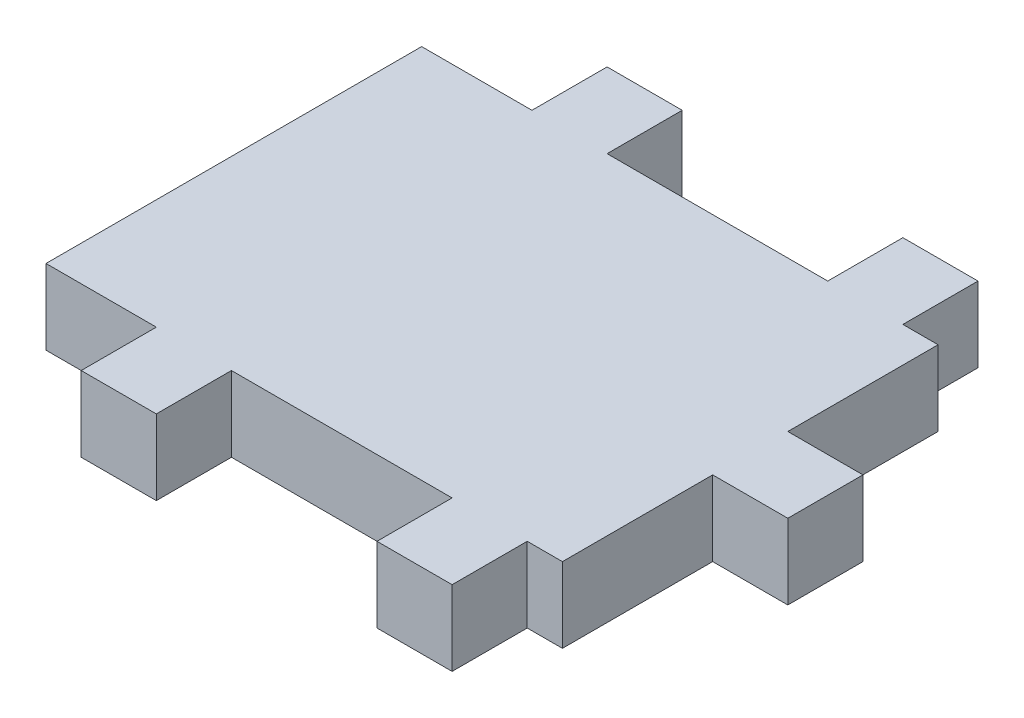
SolidWorks part; units mm, degrees
material "6061 Alloy"
ref_plane "Front" through (0, 0, 0) normal (0, 0, 1) x (1, 0, 0)
ref_plane "Top" through (0, 0, 0) normal (0, 1, 0) x (1, 0, 0)
ref_plane "Right" through (0, 0, 0) normal (1, 0, 0) x (0, 0, -1)
sketch "Sketch3" plane through (0, 0, 0) normal (0, 1, 0) x (1, 0, 0)
  line L1 (-43.65, -31.75) -> (43.65, -31.75)
  line L2 (-43.65, -31.75) -> (-43.65, 31.75)
  line L3 (-43.65, 31.75) -> (43.65, 31.75)
  line L4 (43.65, -31.75) -> (43.65, 31.75)
  line L5 (-43.65, -31.75) -> (43.65, 31.75) construction
  line L6 (-43.65, 31.75) -> (43.65, -31.75) construction
  point P0 (0, 0)
  dimension "D1" = 87.3
  dimension "D2" = 63.5
extrude "Boss-Extrude3" add sketch "Sketch3" along normal blind 12.7
sketch "Sketch4" plane through (43.65, 0, 0) normal (1, 0, 0) x (0, 0, -1)
  line L0 (0, 0) -> (0, 12.7) construction
  line L1 (-31.75, 12.7) -> (31.75, 12.7) construction
  line L3 (-6.35, 0) -> (6.35, 0)
  line L4 (-6.35, 0) -> (-6.35, 12.7)
  line L5 (-6.35, 12.7) -> (6.35, 12.7)
  line L6 (6.35, 0) -> (6.35, 12.7)
  line L7 (-6.35, 0) -> (6.35, 12.7) construction
  line L8 (-6.35, 12.7) -> (6.35, 0) construction
  point P5 (0, 6.35)
  dimension "D1" = 12.7
extrude "Boss-Extrude4" add sketch "Sketch4" along normal blind 12.7
sketch "Sketch5" plane through (0, 0, 31.75) normal (0, 0, 1) x (1, 0, 0)
  line L0 (43.65, 6.35) -> (31.35, 6.35) construction
  line L1 (43.65, 12.7) -> (43.65, 0) construction
  line L2 (-31.35, 6.35) -> (-18.65, 6.35)
  line L3 (31.35, 6.35) -> (-31.35, 6.35) construction
  line L4 (-43.65, 0) -> (43.65, 0) construction
  line L10 (-25, 12.7) -> (-12.3, 12.7)
  line L11 (-25, 12.7) -> (-25, 0)
  line L12 (-25, 0) -> (-12.3, 0)
  line L17 (-12.3, 12.7) -> (-12.3, 0)
  line L18 (-25, 12.7) -> (-12.3, 0) construction
  line L19 (-25, 0) -> (-12.3, 12.7) construction
  line L21 (25, 12.7) -> (37.7, 12.7)
  line L22 (25, 12.7) -> (25, 0)
  line L23 (25, 0) -> (37.7, 0)
  line L24 (37.7, 12.7) -> (37.7, 0)
  line L25 (25, 12.7) -> (37.7, 0) construction
  line L26 (25, 0) -> (37.7, 12.7) construction
  dimension "D1" = 12.3
  dimension "D2" = 12.7
  dimension "D3" = 62.7
  dimension "D4" = 12.7
  dimension "D5" = 12.7
extrude "Boss-Extrude7" add sketch "Sketch5" along normal blind 12.7
mirror "Mirror2" about plane through (0, 0, 0) normal (0, 0, 1) of "Boss-Extrude7"
